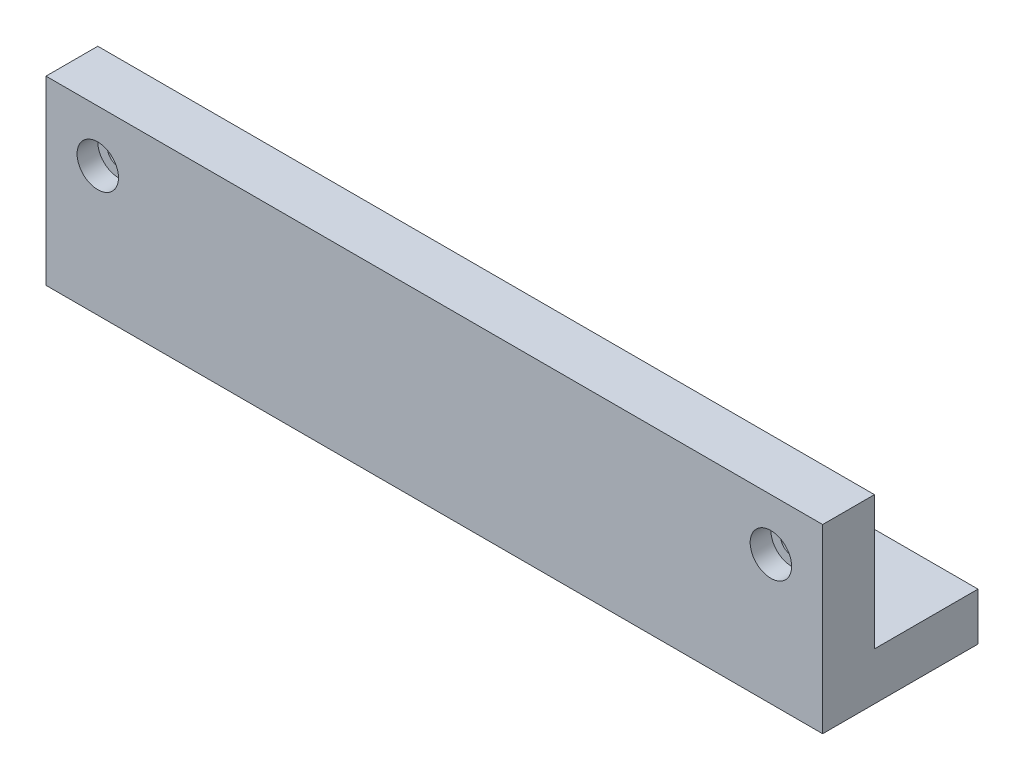
SolidWorks part; units mm, degrees
ref_plane "정면" through (0, 0, 0) normal (0, 0, 1) x (1, 0, 0)
ref_plane "윗면" through (0, 0, 0) normal (0, 1, 0) x (1, 0, 0)
ref_plane "우측면" through (0, 0, 0) normal (1, 0, 0) x (0, 0, -1)
sketch "스케치1" plane through (0, 0, 0) normal (0, 0, 1) x (1, 0, 0)
  line L1 (-25, 2.55) -> (25, 2.55)
  line L2 (-25, 2.55) -> (-25, -2.55)
  line L3 (-25, -2.55) -> (25, -2.55)
  line L4 (25, 2.55) -> (25, -2.55)
  line L5 (-25, 2.55) -> (25, -2.55) construction
  line L6 (-25, -2.55) -> (25, 2.55) construction
  point P0 (0, 0)
  dimension "D1" = 5.1
  dimension "D2" = 50
extrude "보스-돌출1" add sketch "스케치1" along normal blind 4 contours L1 L4 L3 L2
sketch "스케치3" plane through (0, 0, 4) normal (0, 0, 1) x (1, 0, 0)
  line L0 (25, 2.55) -> (25, -2.55) construction
  line L1 (-25, 10) -> (25, 10)
  line L2 (-25, 10) -> (-25, -15)
  line L3 (-25, -15) -> (25, -15)
  line L4 (25, 10) -> (25, -15)
  line L5 (-25, 10) -> (25, -15) construction
  line L6 (-25, -15) -> (25, 10) construction
  line L10 (-25, 2.55) -> (-25, -2.55) construction
  line L11 (-25, -10) -> (25, -10) construction
  point P0 (0, 0)
  dimension "D1" = 0
  dimension "D2" = 25
  dimension "D3" = 5
  dimension "D4" = 20
  dimension "D5" = 10
extrude "보스-돌출2" add sketch "스케치3" along normal blind 10
sketch "스케치4" plane through (-25, 0, 0) normal (-1, 0, 0) x (0, 0, 1)
  line L0 (14, -15) -> (4, -15) construction
  line L1 (4, 10) -> (14, 10)
  line L2 (4, 10) -> (4, -15)
  line L3 (4, -15) -> (14, -15)
  line L4 (14, 10) -> (14, -15)
  line L5 (14, 10) -> (14, -15) construction
extrude "보스-돌출3" add sketch "스케치4" along normal blind 50
ref_plane "평면1" through (0, 0, 0) normal (-1, 0, 0) x (0, 0, 1)
mirror "대칭 복사1" about plane through (0, 0, 0) normal (-1, 0, 0) of "보스-돌출3"
sketch "스케치5" plane through (0, -15, 0) normal (0, -1, 0) x (1, 0, 0)
  line L1 (-75, 14) -> (75, 14)
  line L2 (-75, 14) -> (-75, -16)
  line L3 (-75, -16) -> (75, -16)
  line L4 (75, 14) -> (75, -16)
  dimension "D1" = 30
extrude "보스-돌출4" add sketch "스케치5" along normal blind 10
sketch "스케치6" plane through (0, 0, -16) normal (0, 0, -1) x (-1, 0, 0)
  line L0 (-75, 10) -> (-75, -15) construction
  line L1 (-75, -15) -> (75, -15)
  line L2 (-75, -15) -> (-75, -15.8)
  line L3 (-75, -15.8) -> (75, -15.8)
  line L4 (75, -15) -> (75, -15.8)
  line L5 (75, -15) -> (-75, -15) construction
  line L6 (75, -25) -> (75, -15) construction
  dimension "D1" = 0.8
extrude "컷-돌출1" cut sketch "스케치6" against normal up to vertex
hole_wizard "M4 소켓 머리 캡 나사용 카운터보어1" positions "스케치7" profile "스케치8" counterbore size "M4" standard "KS" end condition through all
sketch "스케치7" plane through (0, 0, 14) normal (0, 0, 1) x (1, 0, 0)
  line L0 (75, 10) -> (-75, 10) construction
  line L1 (75, -25) -> (75, 10) construction
  line L2 (-75, -25) -> (-75, 10) construction
  point P0 (-65, 0)
  point P2 (65, 0)
  dimension "D1" = 10
  dimension "D2" = 10
  dimension "D3" = 10
  dimension "D4" = 10
sketch "스케치8" plane through (-65, 0, 14) normal (1, 0, 0) x (0, -1, 0)
  line L0 (0, 0) -> (0, 30)
  line L1 (0, 30) -> (2.15, 30)
  line L3 (2.15, 30) -> (2.15, 4)
  line L4 (2.15, 4) -> (4, 4)
  line L5 (4, 4) -> (4, 0)
  line L7 (4, 0) -> (0, 0)
  line L11 (0, -6.35) -> (0, 107.95) construction
  dimension "관통 구멍 지름" = 4.3
  dimension "관통 구멍 깊이" = 30
  dimension "카운터보어 지름" = 8
  dimension "카운터보어 깊이" = 4
